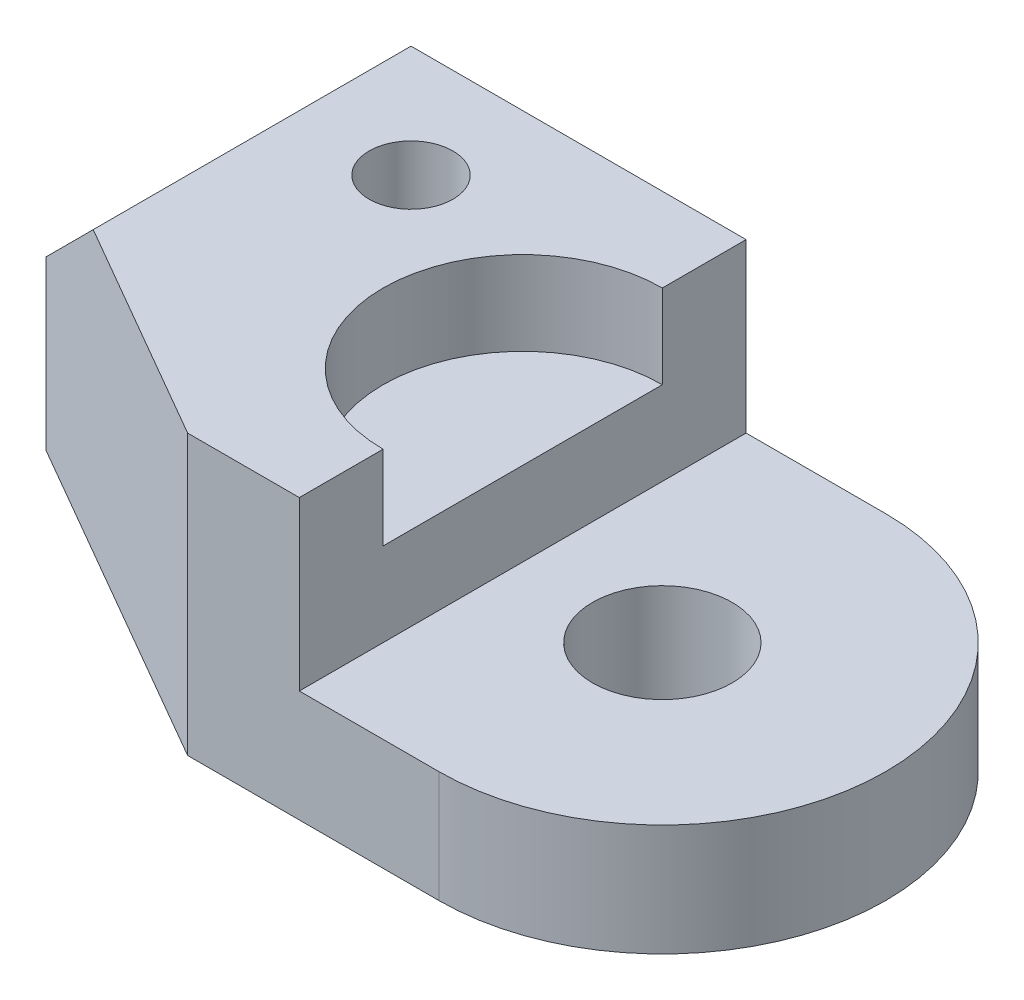
SolidWorks part; units mm, degrees
material "AISI 316 Stainless Steel Sheet (SS)"
ref_plane "Front" through (0, 0, 0) normal (0, 0, 1) x (1, 0, 0)
ref_plane "Top" through (0, 0, 0) normal (0, 1, 0) x (1, 0, 0)
ref_plane "Right" through (0, 0, 0) normal (1, 0, 0) x (0, 0, -1)
sketch "Sketch1" plane through (0, 0, 0) normal (0, 1, 0) x (1, 0, 0)
  line L0 (0, 0) -> (-31.75, 0) construction
  line L1 (-31.75, 50.8) -> (-31.75, -50.8)
  line L2 (-31.75, 50.8) -> (0, 50.8)
  line L3 (-31.75, -50.8) -> (0, -50.8)
  circle A0 centre (0, 0) radius 15.875
  arc A2 (0, -50.8) -> (0, 50.8) centre (0, 0) ccw
  point P7 (-31.75, 0)
extrude "Boss-Extrude1" add sketch "Sketch1" along normal blind 25.4
sketch "Sketch2" plane through (0, 0, 0) normal (0, 1, 0) x (1, 0, 0)
  line L0 (-31.75, 50.8) -> (-133.35, 50.8)
  line L1 (-31.75, 50.8) -> (-31.75, -50.8)
  line L2 (-31.75, -50.8) -> (-57.15, -50.8)
  line L3 (-57.15, -50.8) -> (-133.35, -6.8059)
  line L4 (-57.15, -50.8) -> (-145.7778, -50.8) construction
  line L5 (-133.35, 50.8) -> (-133.35, -6.8059)
  dimension "D1" = 30
  dimension "D2" = 57.6059
  dimension "D3" = 101.6
extrude "Boss-Extrude2" add sketch "Sketch2" along normal blind 63.5
sketch "Sketch3" plane through (0, 0, -50.8) normal (0, 0, -1) x (-1, 0, 0)
  line L0 (133.35, 63.5) -> (133.35, 38.1)
  line L1 (133.35, 63.5) -> (133.35, 0) construction
  line L2 (133.35, 38.1) -> (107.95, 63.5)
  line L3 (133.35, 63.5) -> (107.95, 63.5)
  dimension "D1" = 45
  dimension "D2" = 35.921
extrude "Cut-Extrude2" cut sketch "Sketch3" against normal through all
sketch "Sketch4" plane through (0, 63.5, 0) normal (0, 1, 0) x (1, 0, 0)
  line L0 (-31.75, -50.8) -> (-31.75, 50.8) construction
  line L1 (-31.75, 31.75) -> (-31.75, -31.75)
  arc A0 (-31.75, 31.75) -> (-31.75, -31.75) centre (-31.75, 0) ccw
  dimension "D1" = 31.75
extrude "Cut-Extrude3" cut sketch "Sketch4" against normal blind 19.05
hole_wizard "3/8 (0.75) Diameter Hole1" positions "3DSketch2" profile "Sketch5" hole size "3/8" standard "ANSI Inch" end condition through all
sketch3d "3DSketch2"
  line L0 (-31.75, 63.5, -31.75) -> (-31.75, 63.5, -50.8) construction
  line L1 (-31.75, 63.5, -50.8) -> (-107.95, 63.5, -50.8) construction
  point P0 (-82.55, 63.5, -25.4)
  dimension "D1" = 50.8
  dimension "D2" = 25.4
sketch "Sketch5" plane through (-82.55, 63.5, -25.4) normal (1, 0, 0) x (0, 0, 1)
  line L0 (0, 0) -> (0, 63.5)
  line L1 (0, 63.5) -> (9.525, 63.5)
  line L2 (9.525, 63.5) -> (9.525, 0)
  line L5 (9.525, 0) -> (0, 0)
  line L11 (0, -6.35) -> (0, 107.95) construction
  dimension "Thru Hole Dia." = 19.05
  dimension "Thru Hole Depth" = 63.5
